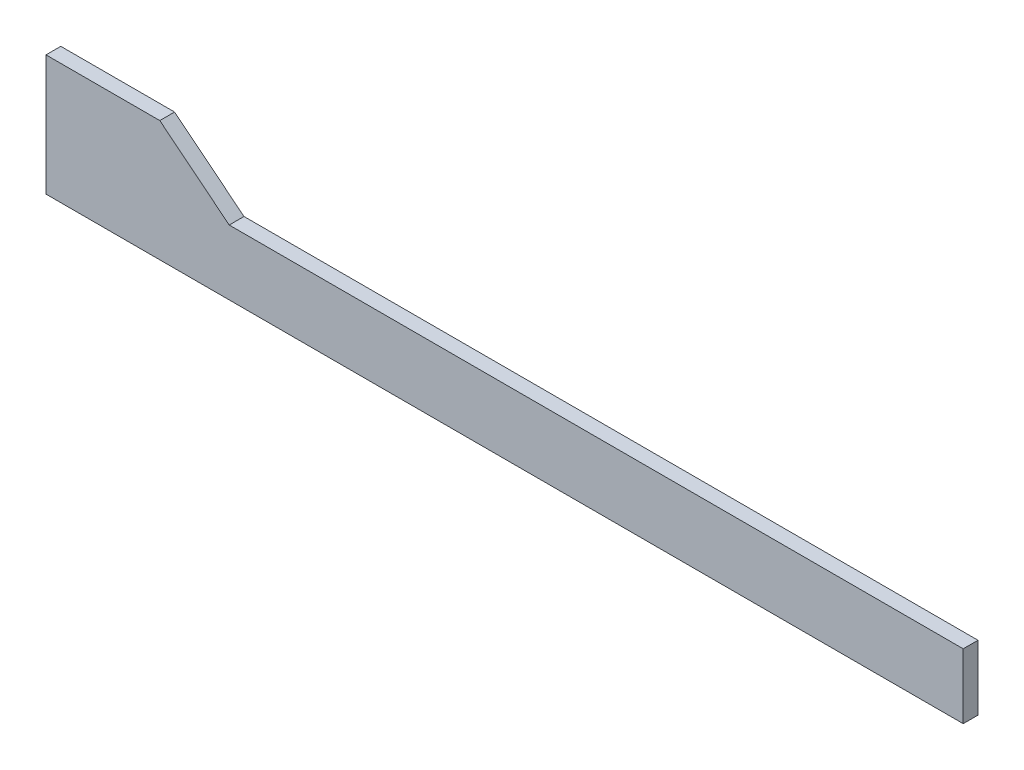
SolidWorks part; units mm, degrees
ref_plane "Alzado" through (0, 0, 0) normal (0, 0, 1) x (1, 0, 0)
ref_plane "Planta" through (0, 0, 0) normal (0, 1, 0) x (1, 0, 0)
ref_plane "Vista lateral" through (0, 0, 0) normal (1, 0, 0) x (0, 0, -1)
sketch "Croquis1" plane through (0, 0, 0) normal (0, 0, 1) x (1, 0, 0)
  line L0 (-403, 53) -> (-403, -53)
  line L1 (-403, -53) -> (403, -53)
  line L2 (403, -53) -> (403, 4)
  line L3 (403, 4) -> (-242, 4)
  line L4 (-242, 4) -> (-303, 53)
  line L5 (-303, 53) -> (-403, 53)
  point P9 (-272.9979, 43.8815)
  point P10 (-297.0229, 22.3855)
  dimension "D1" = 53
  dimension "D2" = 53
  dimension "D3" = 403
  dimension "D4" = 403
  dimension "D5" = 100
  dimension "D6" = 645
  dimension "D7" = 57
extrude "Saliente-Extruir1" add sketch "Croquis1" along normal blind 13
